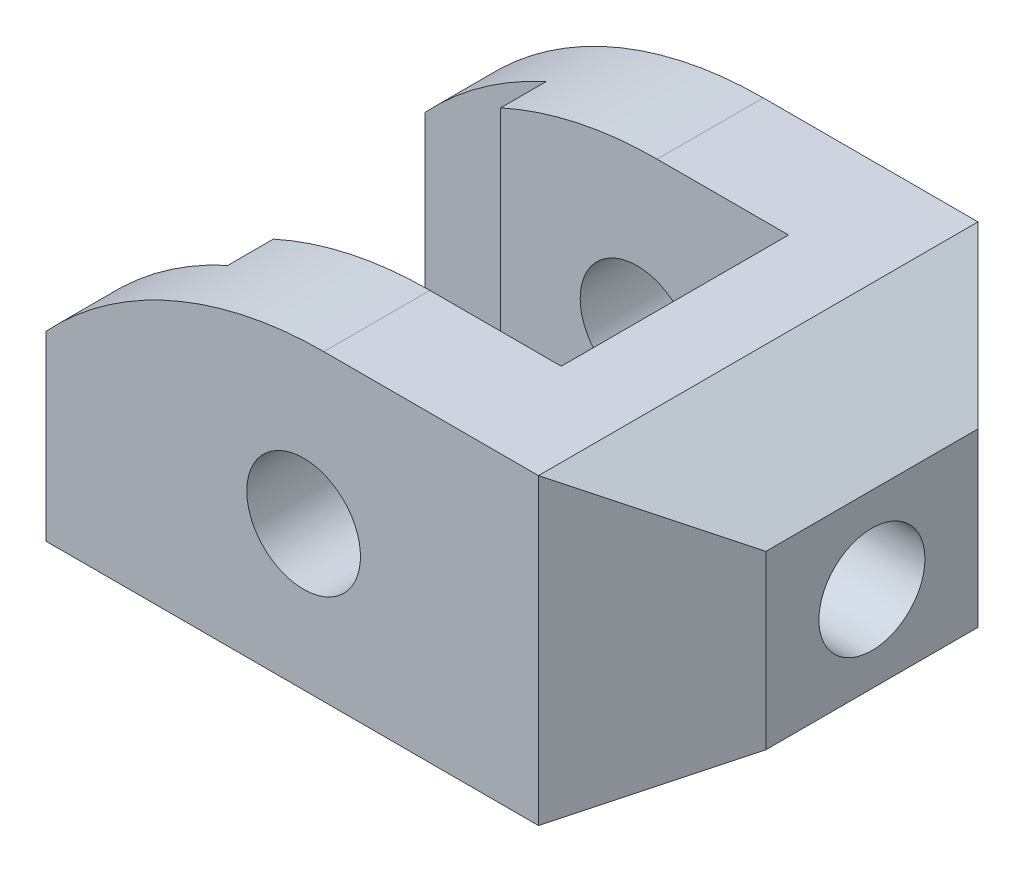
SolidWorks part; units mm, degrees
material "1060 Alloy"
ref_plane "Front Plane" through (0, 0, 0) normal (0, 0, 1) x (1, 0, 0)
ref_plane "Top Plane" through (0, 0, 0) normal (0, 1, 0) x (1, 0, 0)
ref_plane "Right Plane" through (0, 0, 0) normal (1, 0, 0) x (0, 0, -1)
sketch "Sketch2" plane through (0, 0, 0) normal (0, 0, 1) x (1, 0, 0)
  line L0 (0, 0) -> (0, 24)
  line L1 (0, 0) -> (65, 0)
  line L2 (65, 0) -> (80, 8.6603)
  line L3 (80, 8.6603) -> (80, 31.3397)
  line L4 (80, 31.3397) -> (65, 40)
  line L5 (65, 40) -> (36.6606, 40)
  arc A0 (0, 24) -> (36.6606, 40) centre (36.6606, -10) cw
  circle A1 centre (34, 19) radius 7.5
  dimension "D7" = 50
  dimension "D11" = 15
  dimension "D1" = 65
  dimension "D2" = 40
  dimension "D3" = 15
  dimension "D4" = 15
  dimension "D5" = 30
  dimension "D6" = 30
  dimension "D8" = 24
  dimension "D9" = 19
  dimension "D10" = 31
extrude "Boss-Extrude1" add sketch "Sketch2" along normal mid plane 58
sketch "Sketch3" plane through (0, 40, 0) normal (0, 1, 0) x (1, 0, 0)
  line L1 (80, -29) -> (80, 29) construction
  line L5 (0, 0) -> (80, 0) construction
  line L6 (65, 29) -> (80, 29)
  line L7 (80, 29) -> (80, 14)
  line L8 (80, 14) -> (65, 29)
  line L9 (0, 21) -> (16, 21)
  line L10 (0, -29) -> (0, 29) construction
  line L11 (16, 21) -> (16, 15)
  line L12 (16, 15) -> (54, 15)
  line L13 (54, 15) -> (54, -15)
  line L14 (65, -29) -> (65, 29) construction
  line L15 (36.6606, 29) -> (0, 29) construction
  line L16 (80, -29) -> (80, -14)
  line L17 (65, -29) -> (80, -29)
  line L18 (80, -14) -> (65, -29)
  line L19 (16, -15) -> (54, -15)
  line L20 (16, -21) -> (16, -15)
  line L21 (0, -21) -> (16, -21)
  line L22 (0, 21) -> (0, -21)
  point P26 (54, 0)
  dimension "D1" = 45
  dimension "D2" = 11
  dimension "D3" = 8
  dimension "D4" = 6
  dimension "D5" = 16
extrude "Cut-Extrude1" cut sketch "Sketch3" against normal through all
sketch "Sketch4" plane through (80, 0, 0) normal (1, 0, 0) x (0, 0, -1)
  line L0 (-14, 20) -> (14, 20) construction
  line L1 (-14, 8.6603) -> (-14, 31.3397) construction
  line L2 (14, 8.6603) -> (14, 31.3397) construction
  line L3 (0, 31.3397) -> (0, 8.6603) construction
  line L4 (-14, 31.3397) -> (14, 31.3397) construction
  line L5 (-14, 8.6603) -> (14, 8.6603) construction
  circle A0 centre (0, 20) radius 7
  dimension "D1" = 14
extrude "Cut-Extrude2" cut sketch "Sketch4" against normal through all
equation "\"A\"= 58"
equation "\"B\"= 40"
equation "\"C\"= 65"
